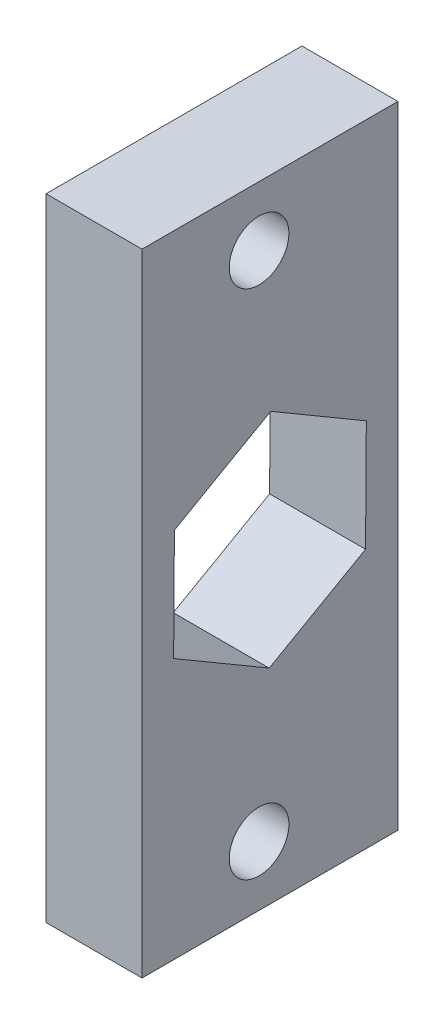
SolidWorks part; units mm, degrees
material "PLA"
ref_plane "Front Plane" through (0, 0, 0) normal (1, 0, 0) x (0, 1, 0)
ref_plane "Top Plane" through (0, 0, 0) normal (0, 0, 1) x (0, 1, 0)
ref_plane "Right Plane" through (0, 0, 0) normal (0, 1, 0) x (-1, 0, 0)
sketch "Sketch1" plane through (0, 0, 0) normal (1, 0, 0) x (0, -1, 0)
  line L20 (-19.7286, 19.3495) -> (-19.7286, 3.3495)
  line L21 (-19.7286, 3.3495) -> (19.738, 3.3495)
  line L22 (19.738, 3.3495) -> (19.738, 19.3495)
  line L23 (19.738, 19.3495) -> (-19.7286, 19.3495)
  line L25 (-3.4179, 17.3733) -> (-6.9233, 11.3974)
  line L26 (-6.9233, 11.3974) -> (-3.5007, 5.3736)
  line L27 (-3.5007, 5.3736) -> (3.4273, 5.3258)
  line L28 (3.4273, 5.3258) -> (6.9328, 11.3017)
  line L29 (6.9328, 11.3017) -> (3.5102, 17.3255)
  line L30 (3.5102, 17.3255) -> (-3.4179, 17.3733)
  circle A2 centre (16, 10.6667) radius 1.8667
  circle A3 centre (-16, 10.6667) radius 1.8667
  dimension "D1" = 16
  dimension "D2" = 12
extrude "Boss-Extrude1" add sketch "Sketch1" along normal blind 6 contours L21 L22 L23 L20
